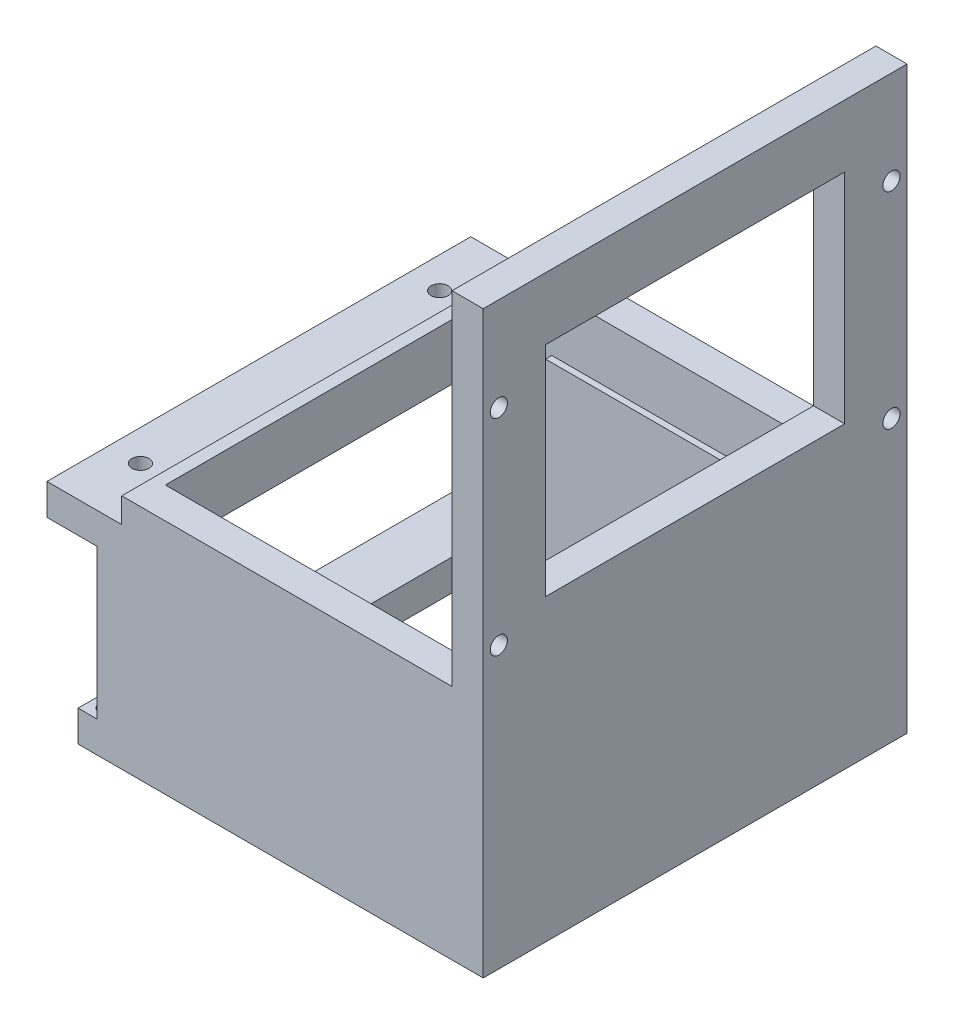
SolidWorks part; units mm, degrees
ref_plane "Front Plane" through (0, 0, 0) normal (0, 0, 1) x (1, 0, 0)
ref_plane "Top Plane" through (0, 0, 0) normal (0, 1, 0) x (1, 0, 0)
ref_plane "Right Plane" through (0, 0, 0) normal (1, 0, 0) x (0, 0, -1)
sketch "Sketch1" plane through (0, 0, 0) normal (0, 1, 0) x (1, 0, 0)
  line L1 (-29, -34) -> (29, -34)
  line L2 (-29, -34) -> (-29, 34)
  line L3 (-29, 34) -> (29, 34)
  line L4 (29, -34) -> (29, 34)
  line L5 (-29, -34) -> (29, 34) construction
  line L6 (-29, 34) -> (29, -34) construction
  point P0 (0, 0)
  dimension "D1" = 68
  dimension "D2" = 58
extrude "Boss-Extrude1" add sketch "Sketch1" along normal blind 4
sketch "Sketch2" plane through (0, 4, 0) normal (0, 1, 0) x (1, 0, 0)
  line L0 (-29, -34) -> (29, -34) construction
  line L1 (29, 34) -> (24, 34)
  line L2 (29, 34) -> (29, -34)
  line L3 (29, -34) -> (24, -34)
  line L4 (24, 34) -> (24, -34)
  dimension "D1" = 5
extrude "Boss-Extrude2" add sketch "Sketch2" along normal blind 55
sketch "Sketch3" plane through (0, 0, 0) normal (0, -1, 0) x (1, 0, 0)
  line L1 (29, 34) -> (-41, 34)
  line L2 (29, 34) -> (29, -34)
  line L3 (29, -34) -> (-41, -34)
  line L4 (-41, 34) -> (-41, -34)
  dimension "D1" = 70
extrude "Boss-Extrude3" add sketch "Sketch3" along normal blind 5
sketch "Sketch4" plane through (0, -5, 0) normal (0, -1, 0) x (1, 0, 0)
  line L0 (29, 34) -> (-41, 34) construction
  line L1 (-41, 34) -> (-41, -34) construction
  line L2 (55, 0) -> (-55, 0) construction
  circle A0 centre (-36, 24) radius 1.375
  circle A1 centre (-36, -24) radius 1.375
  dimension "D1" = 2.75
  dimension "D2" = 10
  dimension "D3" = 5
extrude "Cut-Extrude1" cut sketch "Sketch4" against normal up to next
sketch "Sketch5" plane through (29, 0, 0) normal (1, 0, 0) x (0, 0, -1)
  line L0 (-34, 59) -> (-34, -5) construction
  line L1 (-34, 59) -> (34, 59) construction
  line L2 (34, 4) -> (-34, 4) construction
  line L3 (0, 55) -> (0, -55) construction
  line L12 (-24, 14) -> (24, 14)
  line L13 (-24, 49) -> (-24, 14)
  line L14 (24, 49) -> (-24, 49)
  line L15 (24, 14) -> (24, 49)
  line L16 (-24, 14) -> (24, 14)
  line L17 (-24, 49) -> (-24, 14)
  line L18 (24, 49) -> (-24, 49)
  line L19 (24, 14) -> (24, 49)
  circle A0 centre (-31.5, 44) radius 1.375
  circle A1 centre (-31.5, 11) radius 1.375
  circle A2 centre (31.5, 11) radius 1.375
  circle A3 centre (31.5, 44) radius 1.375
  dimension "D1" = 2.75
  dimension "D5" = 2.75
  dimension "D2" = 2.5
  dimension "D3" = 15
  dimension "D4" = 2.5
  dimension "D6" = 7
  dimension "D7" = 10
extrude "Cut-Extrude2" cut sketch "Sketch5" against normal up to next
sketch "Sketch6" plane through (0, 4, 0) normal (0, 1, 0) x (1, 0, 0)
  line L8 (19, -29) -> (19, 29)
  line L9 (19, 29) -> (-24, 29)
  line L10 (-24, 29) -> (-24, -29)
  line L11 (-24, -29) -> (19, -29)
  line L12 (19, -29) -> (19, 29)
  line L18 (-29, 34) -> (-29, -34) construction
  line L19 (19, 29) -> (-27, 29)
  line L20 (19, 29) -> (19, -29)
  line L21 (19, -29) -> (-27, -29)
  line L22 (-27, 29) -> (-27, -29)
  dimension "D2" = 2
  dimension "D1" = 5
extrude "Cut-Extrude4" cut sketch "Sketch6" against normal up to next
sketch "Sketch7" plane through (0, -5, 0) normal (0, -1, 0) x (1, 0, 0)
  line L0 (-41, -34) -> (29, -34) construction
  line L1 (29, 34) -> (-33, 34)
  line L2 (29, 34) -> (29, -34)
  line L3 (29, -34) -> (-33, -34)
  line L4 (-33, 34) -> (-33, -34)
  line L5 (23, 28) -> (23, -28)
  line L6 (23, -28) -> (-27, -28)
  line L7 (-27, 28) -> (-27, -28)
  line L8 (23, 28) -> (-27, 28)
  dimension "D2" = 62
  dimension "D1" = 6
extrude "Boss-Extrude4" add sketch "Sketch7" along normal blind 24
sketch "Sketch8" plane through (0, -29, 0) normal (0, -1, 0) x (1, 0, 0)
  line L0 (26.5, -31.5) -> (26.5, 31.5)
  line L1 (29, -34) -> (-36, -34)
  line L2 (29, -34) -> (29, 34)
  line L3 (29, 34) -> (-36, 34)
  line L4 (-36, -34) -> (-36, 34)
  line L5 (26.5, 31.5) -> (-33.5, 31.5)
  line L6 (-33.5, -31.5) -> (-33.5, 31.5)
  line L7 (26.5, -31.5) -> (-33.5, -31.5)
  line L8 (38.5, 0) -> (-38.5, 0) construction
  circle A0 centre (26.5, -31.5) radius 1.5
  circle A1 centre (-33.5, -31.5) radius 1.5
  circle A2 centre (-33.5, 31.5) radius 1.5
  circle A3 centre (26.5, 31.5) radius 1.5
  circle A4 centre (-3.5, 0) radius 1.5
  line M9 (29, -34) -> (29, 34)
  line M10 (29, 34) -> (-33, 34)
  line M11 (-33, 34) -> (-33, -34)
  line M12 (-33, -34) -> (29, -34)
  line M13 (-27, 28) -> (23, 28)
  line M14 (23, 28) -> (23, -28)
  line M15 (23, -28) -> (-27, -28)
  line M16 (-27, -28) -> (-27, 28)
  dimension "D3" = 3
  dimension "D4" = 3
  dimension "D5" = 3
  dimension "D1" = 65
  dimension "D2" = 2.5
extrude "Boss-Extrude5" add sketch "Sketch8" along normal blind 5 contours L5 A3 L0 A0 L7 A1 A2 M11 M12 M9 M10 | L6 A2 L3 L4 L1 A1 M11 | L0 A3 L5 A2 A1 L7 A0 M11 M16 M13 M14 M15 | A2 L6 A1 M11 | M13 M16 M15 M14
sketch "Sketch9" plane through (0, -29, 0) normal (0, 1, 0) x (1, 0, 0)
  line L1 (-27, 28) -> (23, 28)
  line L2 (-27, 28) -> (-27, -28)
  line L3 (-27, -28) -> (23, -28)
  line L4 (23, 28) -> (23, -28)
extrude "Cut-Extrude5" cut sketch "Sketch9" against normal blind 10
sketch "Sketch10" plane through (-33, 0, 0) normal (-1, 0, 0) x (0, 0, 1)
  line L0 (34, -5) -> (-34, -5) construction
  line L1 (-29, -5) -> (29, -5)
  line L2 (-29, -5) -> (-29, -29)
  line L3 (-29, -29) -> (29, -29)
  line L4 (29, -5) -> (29, -29)
  line L5 (-34, -29) -> (34, -29) construction
  line L6 (-34, -29) -> (-34, -5) construction
  line L7 (34, -29) -> (34, -5) construction
  dimension "D1" = 5
  dimension "D2" = 5
extrude "Cut-Extrude6" cut sketch "Sketch10" against normal blind 10
